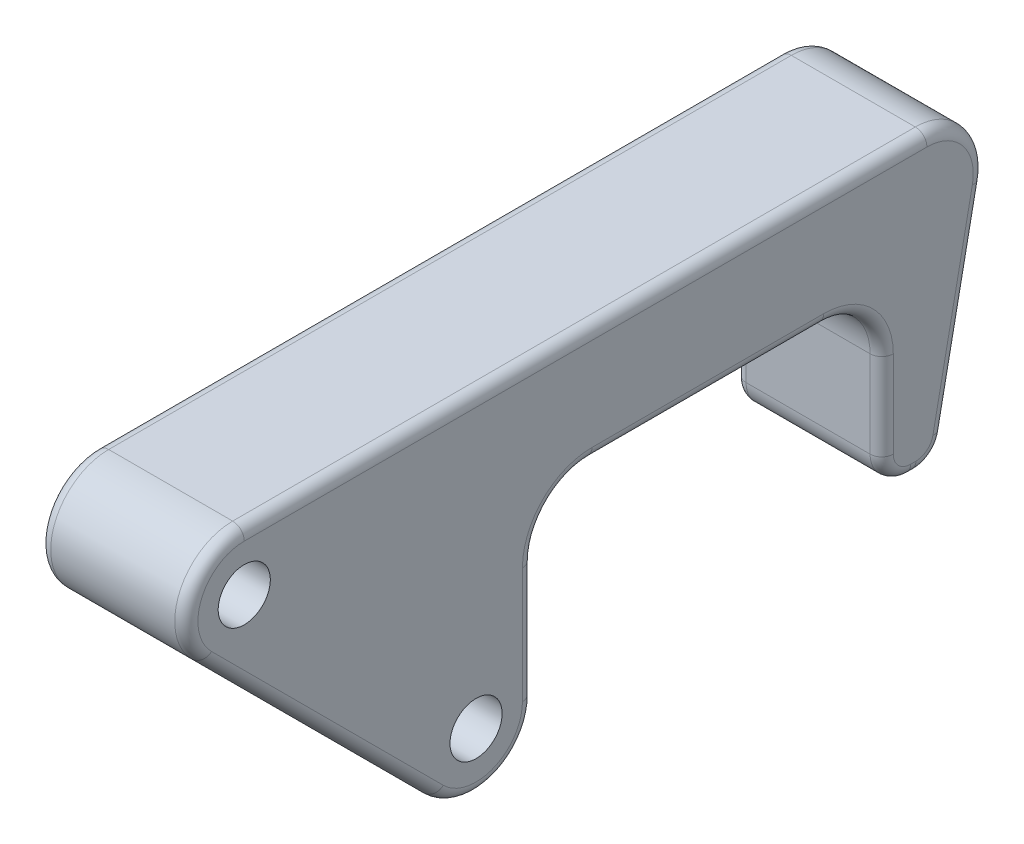
SolidWorks part; units mm, degrees
ref_plane "Front Plane" through (0, 0, 0) normal (0, 0, 1) x (1, 0, 0)
ref_plane "Top Plane" through (0, 0, 0) normal (0, 1, 0) x (1, 0, 0)
ref_plane "Right Plane" through (0, 0, 0) normal (1, 0, 0) x (0, 0, -1)
sketch "Sketch1" plane through (0, 0, 0) normal (1, 0, 0) x (0, 0, -1)
  line L6 (-3.5355, -3.5355) -> (16.4645, -23.5355)
  line L7 (0, 5) -> (65, 5)
  line L8 (55, -20) -> (60, -20)
  line L9 (55, -20) -> (55, -5)
  line L10 (55, -5) -> (25, -5)
  line L11 (25, -5) -> (25, -20)
  line L12 (60, -20) -> (65, 5)
  circle A3 centre (0, 0) radius 2.25
  circle A4 centre (20, -20) radius 2.25
  circle A5 centre (0, 0) radius 5
  circle A6 centre (20, -20) radius 5
  dimension "D2" = 4.5
  dimension "D1" = 4.5
  dimension "D3" = 10
  dimension "D4" = 10
  dimension "D5" = 10
  dimension "D6" = 15
  dimension "D7" = 30
  dimension "D8" = 10
  dimension "D9" = 20
  dimension "D10" = 20
  dimension "D11" = 5
extrude "Boss-Extrude1" add sketch "Sketch1" along normal blind 12.7
fillet "Fillet1" radius 5 3 edges at (6.35, -5, -55) (6.35, 5, -65) (6.35, -5, -25)
fillet "Fillet2" radius 2.5 2 edges at (6.35, -20, -60) (6.35, -20, -55)
fillet "Fillet3" radius 1 28 edges at (12.7, -6.4645, -53.5355) (0, -6.4645, -53.5355) (0, -13.75, -55) (12.7, -13.75, -55) (12.7, -19.2678, -55.7322) (0, -19.2678, -55.7322) (0, -20, -57.7252) (12.7, -20, -57.7252) (12.7, -19.4334, -59.5355) (0, -19.4334, -59.5355) (12.7, -9.4854, -62.1029) (0, -9.4854, -62.1029) (12.7, 3.1699, -62.7677) (0, 3.1699, -62.7677) (12.7, 5, -29.4505) (0, 5, -29.4505) (0, 1.9134, 4.6194) (12.7, 1.9134, 4.6194) (0, -13.5355, -6.4645) (12.7, -13.5355, -6.4645) (0, -24.6194, -21.9134) (12.7, -24.6194, -21.9134) (0, -15, -25) (12.7, -15, -25) (12.7, -6.4645, -26.4645) (0, -6.4645, -26.4645) (0, -5, -40) (12.7, -5, -40)
